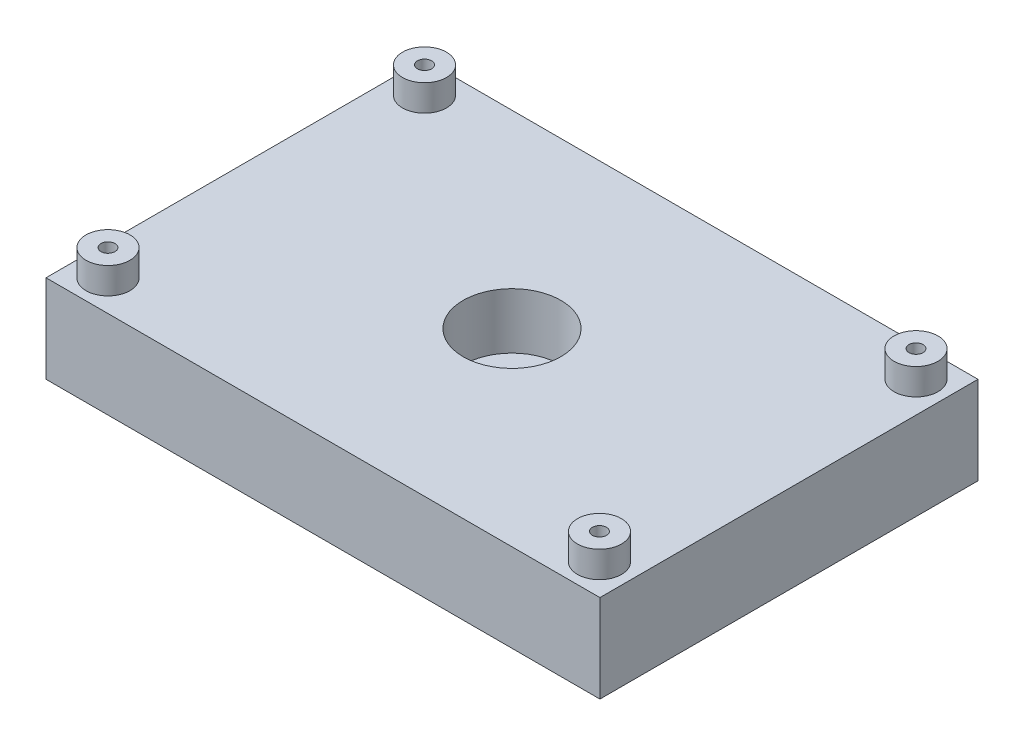
SolidWorks part; units mm, degrees
ref_plane "Front Plane" through (0, 0, 0) normal (0, 0, 1) x (1, 0, 0)
ref_plane "Top Plane" through (0, 0, 0) normal (0, 1, 0) x (1, 0, 0)
ref_plane "Right Plane" through (0, 0, 0) normal (1, 0, 0) x (0, 0, -1)
sketch "Sketch1" plane through (0, 0, 0) normal (0, 1, 0) x (1, 0, 0)
  line L1 (31.5, 21.5) -> (-31.5, 21.5)
  line L2 (31.5, 21.5) -> (31.5, -21.5)
  line L3 (31.5, -21.5) -> (-31.5, -21.5)
  line L4 (-31.5, 21.5) -> (-31.5, -21.5)
  line L5 (31.5, 21.5) -> (-31.5, -21.5) construction
  line L6 (31.5, -21.5) -> (-31.5, 21.5) construction
  point P0 (0, 0)
  dimension "D1" = 43
  dimension "D2" = 63
extrude "Boss-Extrude1" add sketch "Sketch1" along normal blind 10
hole_wizard "CBORE for 1/4 Socket Head Cap Screw1" positions "Sketch2" profile "Sketch4" counterbore size "1/4" standard "ANSI Inch" end condition through all
sketch "Sketch2" plane through (0, 10, 0) normal (0, 1, 0) x (1, 0, 0)
  point P0 (0, 0)
sketch "Sketch4" plane through (0, 10, 0) normal (1, 0, 0) x (0, 0, 1)
  line L0 (0, 0) -> (0, 10)
  line L1 (0, 10) -> (3.3782, 10)
  line L3 (3.3782, 10) -> (3.3782, 6.35)
  line L4 (3.3782, 6.35) -> (5.5562, 6.35)
  line L5 (5.5562, 6.35) -> (5.5563, 0)
  line L7 (5.5563, 0) -> (0, 0)
  line L11 (0, -6.35) -> (0, 107.95) construction
  dimension "Thru Hole Dia." = 6.7564
  dimension "Thru Hole Depth" = 10
  dimension "C'Bore Dia." = 11.1125
  dimension "C'Bore Depth" = 6.35
sketch "Sketch6" plane through (0, 10, 0) normal (0, 1, 0) x (1, 0, 0)
  line L1 (27.95, 18) -> (-27.95, 18) construction
  line L2 (27.95, 18) -> (27.95, -18) construction
  line L3 (27.95, -18) -> (-27.95, -18) construction
  line L4 (-27.95, 18) -> (-27.95, -18) construction
  line L5 (27.95, 18) -> (-27.95, -18) construction
  line L6 (27.95, -18) -> (-27.95, 18) construction
  circle A0 centre (-27.95, 18) radius 2.5
  circle A1 centre (27.95, 18) radius 2.5
  circle A2 centre (27.95, -18) radius 2.5
  circle A3 centre (-27.95, -18) radius 2.5
  point P0 (0, 0)
  dimension "D3" = 5
  dimension "D1" = 36
  dimension "D2" = 55.9
extrude "Boss-Extrude2" add sketch "Sketch6" along normal blind 3
hole_wizard "M2x0.4 Tapped Hole1" positions "Sketch7" profile "Sketch9" tap size "M2x0.4" standard "ANSI Metric" end condition through all
sketch "Sketch7" plane through (0, 13, 0) normal (0, 1, 0) x (1, 0, 0)
  point P0 (-27.95, 18)
  point P3 (27.95, 18)
  point P6 (27.95, -18)
  point P9 (-27.95, -18)
sketch "Sketch9" plane through (-27.95, 13, -18) normal (1, 0, 0) x (0, 0, 1)
  line L0 (0, 0) -> (0, 13)
  line L1 (0, 13) -> (0.8, 13)
  line L2 (0.8, 13) -> (0.8, 0)
  line L5 (0.8, 0) -> (0, 0)
  line L11 (0, -6.35) -> (0, 107.95) construction
  dimension "Thru Tap Drill Dia." = 1.6
  dimension "Thru Tap Drill Depth" = 13
cosmetic thread "Hole Thread1" parameters "D2"=2
cosmetic thread "Hole Thread2" parameters "D2"=2
cosmetic thread "Hole Thread3" parameters "D2"=2
cosmetic thread "Hole Thread4" parameters "D2"=2
